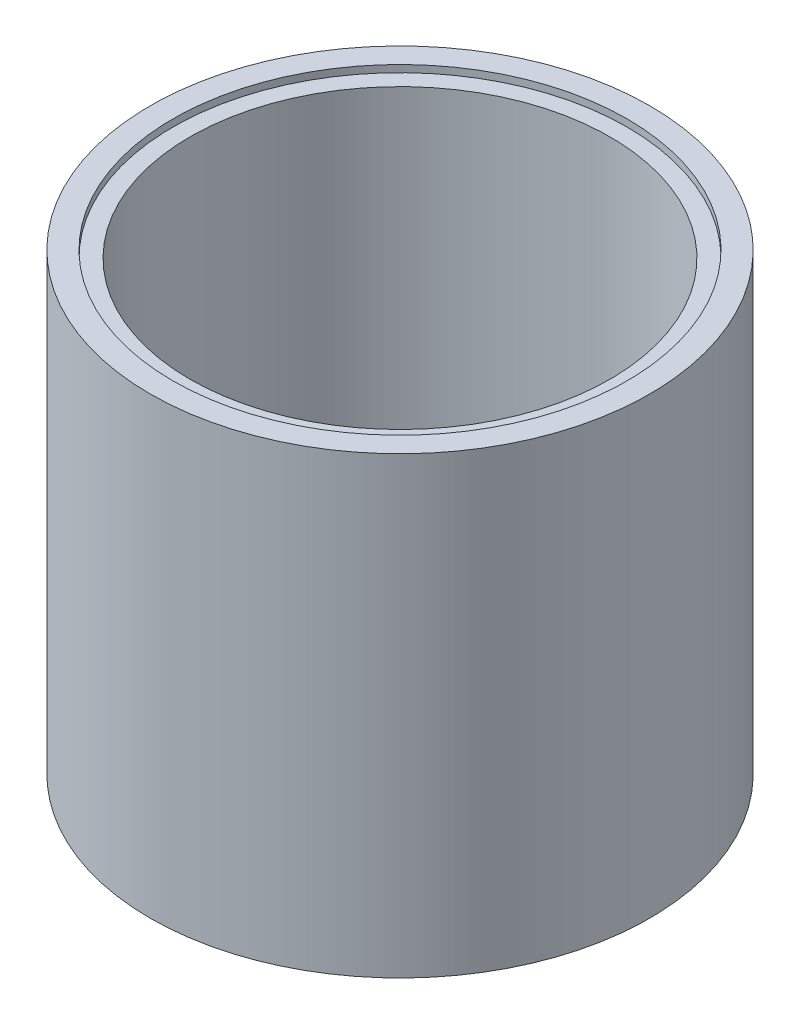
SolidWorks part; units mm, degrees
ref_plane "Front Plane" through (0, 0, 0) normal (0, 0, 1) x (1, 0, 0)
ref_plane "Top Plane" through (0, 0, 0) normal (0, 1, 0) x (1, 0, 0)
ref_plane "Right Plane" through (0, 0, 0) normal (1, 0, 0) x (0, 0, -1)
sketch "Sketch1" plane through (0, 0, 0) normal (0, 1, 0) x (1, 0, 0)
  circle A0 centre (0, 0) radius 46.99
  circle A1 centre (0, 0) radius 55.88
extrude "Boss-Extrude4" add sketch "Sketch1" against normal blind 101.6
sketch "Sketch3" plane through (0, 0, 0) normal (0, 1, 0) x (1, 0, 0)
  circle A0 centre (0, 0) radius 50.8
extrude "Cut-Extrude3" cut sketch "Sketch3" against normal blind 1.5875
hole_wizard "1/4-28 Tapped Hole1" positions "3DSketch2" profile "Sketch7" tap size "1/4-28" standard "ANSI Inch"
sketch3d "3DSketch2"
  point P0 (-54.7815, -84.35, 11.0256)
  point P3 (-54.7815, -84.35, 11.0256)
  point P5 (-54.7815, -84.35, 11.0256)
  point P8 (65.1157, -82.5507, 0)
  point P10 (62.6081, -85.1054, 0)
  point P12 (64.4935, -83.9361, 0)
  point P14 (-54.7815, -84.35, 11.0256)
sketch "Sketch7" plane through (-54.7815, -84.35, 11.0256) normal (0, 1, 0) x (0.1973, 0, 0.9803)
  line L0 (0, 0) -> (0, 8.89)
  line L1 (0, 8.89) -> (2.7051, 8.89)
  line L2 (2.7051, 8.89) -> (2.7051, 0)
  line L5 (2.7051, 0) -> (0, 0)
  line L11 (0, -6.35) -> (0, 107.95) construction
  dimension "Thru Tap Drill Dia." = 5.4102
  dimension "Thru Tap Drill Depth" = 8.89
cosmetic thread "Hole Thread1" parameters "D2"=6.35
